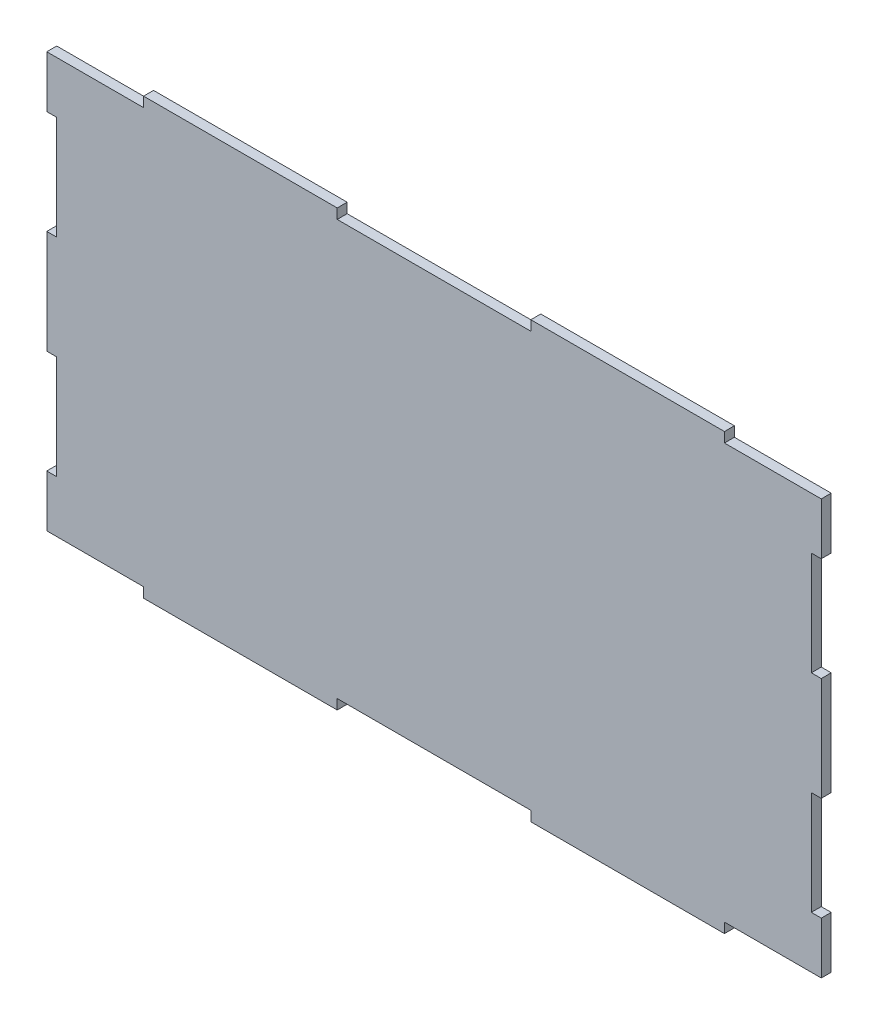
SolidWorks part; units mm, degrees
ref_plane "前视基准面" through (0, 0, 0) normal (0, 0, 1) x (1, 0, 0)
ref_plane "上视基准面" through (0, 0, 0) normal (0, 1, 0) x (1, 0, 0)
ref_plane "右视基准面" through (0, 0, 0) normal (1, 0, 0) x (0, 0, -1)
sketch "草图1" plane through (0, 0, 0) normal (0, 0, 1) x (1, 0, 0)
  line L5 (140, -75) -> (105, -75)
  line L6 (105, -75) -> (105, -78.6)
  line L7 (-140, 75) -> (-105, 75)
  line L8 (35, 75) -> (35, 78.6)
  line L9 (-105, 75) -> (-105, 78.6)
  line L10 (-105, 78.6) -> (-35, 78.6)
  line L11 (-35, 75) -> (-35, 78.6)
  line L12 (35, 75) -> (-35, 75)
  line L13 (105, 78.6) -> (35, 78.6)
  line L14 (105, 75) -> (105, 78.6)
  line L15 (140, 75) -> (105, 75)
  line L16 (105, -78.6) -> (35, -78.6)
  line L17 (35, -75) -> (-35, -75)
  line L18 (-35, -75) -> (-35, -78.6)
  line L19 (-105, -78.6) -> (-35, -78.6)
  line L20 (-105, -75) -> (-105, -78.6)
  line L21 (35, -75) -> (35, -78.6)
  line L22 (-140, -75) -> (-105, -75)
  line L23 (-140, 75) -> (-140, 56.25)
  line L24 (-140, -18.75) -> (-136.4, -18.75)
  line L25 (-140, 56.25) -> (-136.4, 56.25)
  line L26 (-136.4, 56.25) -> (-136.4, 18.75)
  line L27 (-140, 18.75) -> (-136.4, 18.75)
  line L28 (-140, 18.75) -> (-140, -18.75)
  line L29 (-136.4, -56.25) -> (-136.4, -18.75)
  line L30 (-140, -56.25) -> (-136.4, -56.25)
  line L31 (-140, -75) -> (-140, -56.25)
  line L32 (140, -75) -> (140, -56.25)
  line L33 (140, -56.25) -> (136.4, -56.25)
  line L34 (136.4, -56.25) -> (136.4, -18.75)
  line L35 (140, 18.75) -> (140, -18.75)
  line L36 (140, 18.75) -> (136.4, 18.75)
  line L37 (136.4, 56.25) -> (136.4, 18.75)
  line L38 (140, 56.25) -> (136.4, 56.25)
  line L39 (140, -18.75) -> (136.4, -18.75)
  line L40 (140, 75) -> (140, 56.25)
  point P0 (0, 0)
  point P14 (-70, 78.6)
  point P17 (70, 78.6)
  point P26 (70, -78.6)
  point P27 (-70, -78.6)
  point P34 (-136.4, 37.5)
  point P37 (-136.4, -37.5)
  point P46 (136.4, -37.5)
  point P47 (136.4, 37.5)
  dimension "D1" = 280
  dimension "D2" = 150
extrude "凸台-拉伸1" add sketch "草图1" along normal blind 3.6
